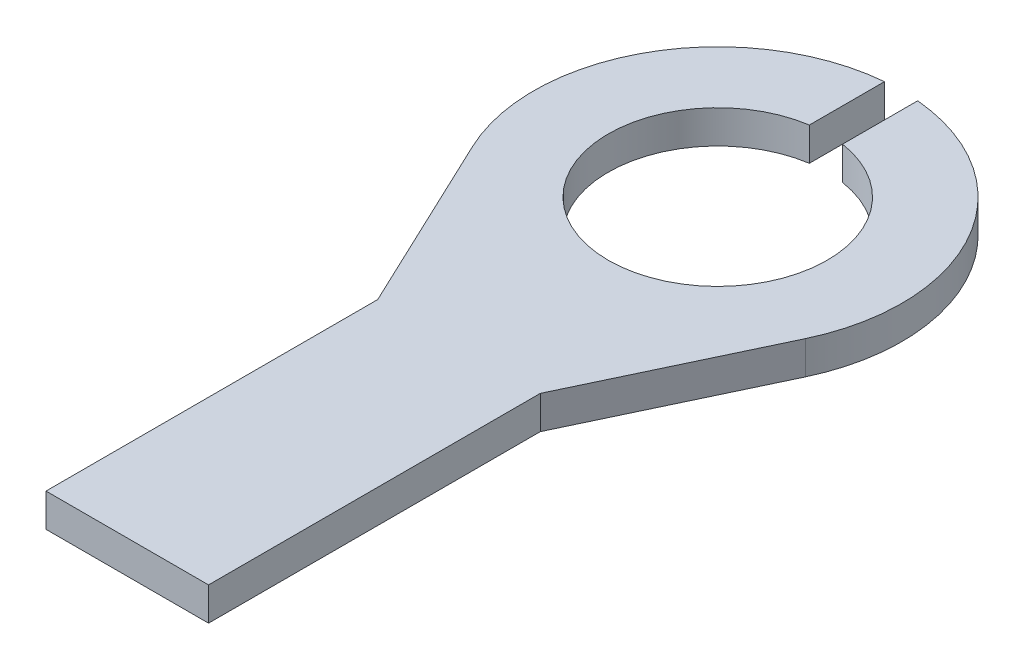
SolidWorks part; units mm, degrees
ref_plane "Front Plane" through (0, 0, 0) normal (0, 0, 1) x (1, 0, 0)
ref_plane "Top Plane" through (0, 0, 0) normal (0, 1, 0) x (1, 0, 0)
ref_plane "Right Plane" through (0, 0, 0) normal (1, 0, 0) x (0, 0, -1)
sketch "Sketch1" plane through (0, 0, 0) normal (0, 1, 0) x (1, 0, 0)
  line L0 (1.2743, -0.6028) -> (0.6223, -1.9812)
  line L1 (-1.2743, -0.6028) -> (-0.6223, -1.9812)
  line L2 (-0.6223, -1.2649) -> (-0.6223, -4.5212)
  line L3 (-0.6223, -4.5212) -> (0.6223, -4.5212)
  line L4 (0.6223, -4.5212) -> (0.6223, -1.2649)
  line L5 (-0.127, 1.404) -> (-0.127, 0.8285)
  line L6 (0.127, 1.404) -> (0.127, 0.8285)
  line L7 (-0.127, 1.1162) -> (0.127, 1.1162) construction
  line L8 (0, -4.5212) -> (0, -1.4097) construction
  circle A0 centre (0, 0) radius 0.8382
  circle A1 centre (0, 0) radius 1.4097
  point P14 (0, -4.5212)
  dimension "D1" = 1.6764
  dimension "D2" = 2.8194
  dimension "D3" = 1.2446
  dimension "D4" = 4.5212
  dimension "D5" = 2.54
  dimension "D6" = 2.54
  dimension "D7" = 0.254
extrude "Boss-Extrude1" add sketch "Sketch1" along normal blind 0.254 contours A1 L6 A0 L5 | A1 L4 L0 | A1 L2 L3 L4 | A1 L1 L2
equation "\"D4@Sketch1\"=0.145in + \"D1@Sketch1\"/2"
equation "\"D6@Sketch1\"=\"D5@Sketch1\""
